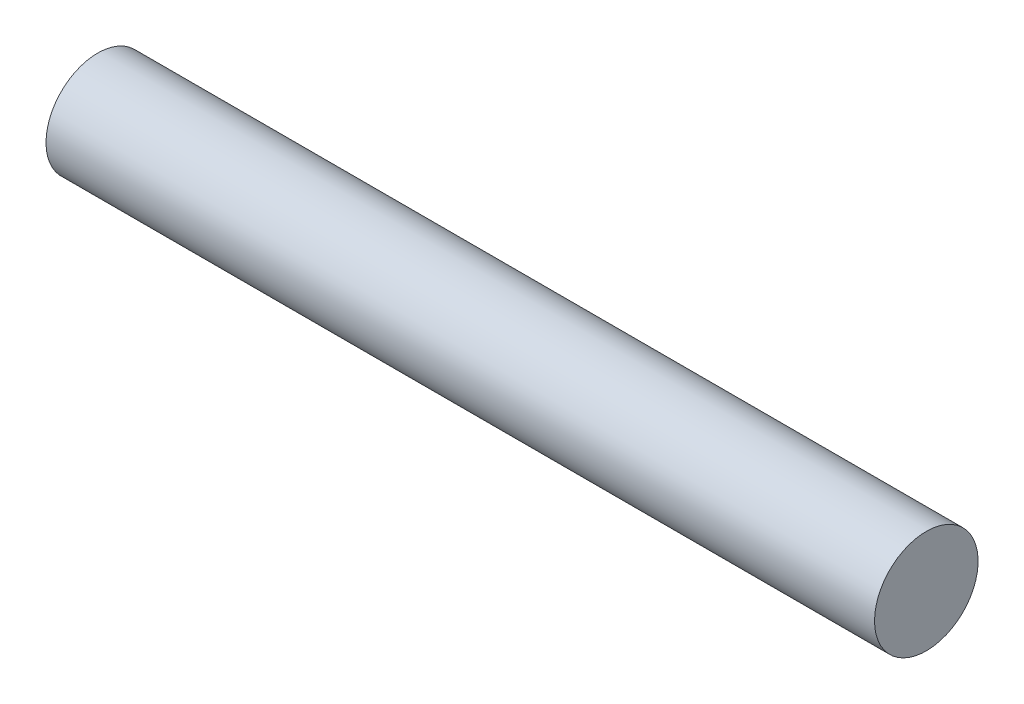
SolidWorks part; units mm, degrees
material "6061 Alloy"
ref_plane "Front Plane" through (0, 0, 0) normal (0, 0, 1) x (1, 0, 0)
ref_plane "Top Plane" through (0, 0, 0) normal (0, 1, 0) x (1, 0, 0)
ref_plane "Right Plane" through (0, 0, 0) normal (1, 0, 0) x (0, 0, -1)
sketch "Croquis2" plane through (0, 0, 0) normal (1, 0, 0) x (0, 0, -1)
  circle A0 centre (0, 0) radius 2.3813
  dimension "D1" = 4.7625
extrude "Saliente-Extruir1" add sketch "Croquis2" along normal mid plane 38.1
